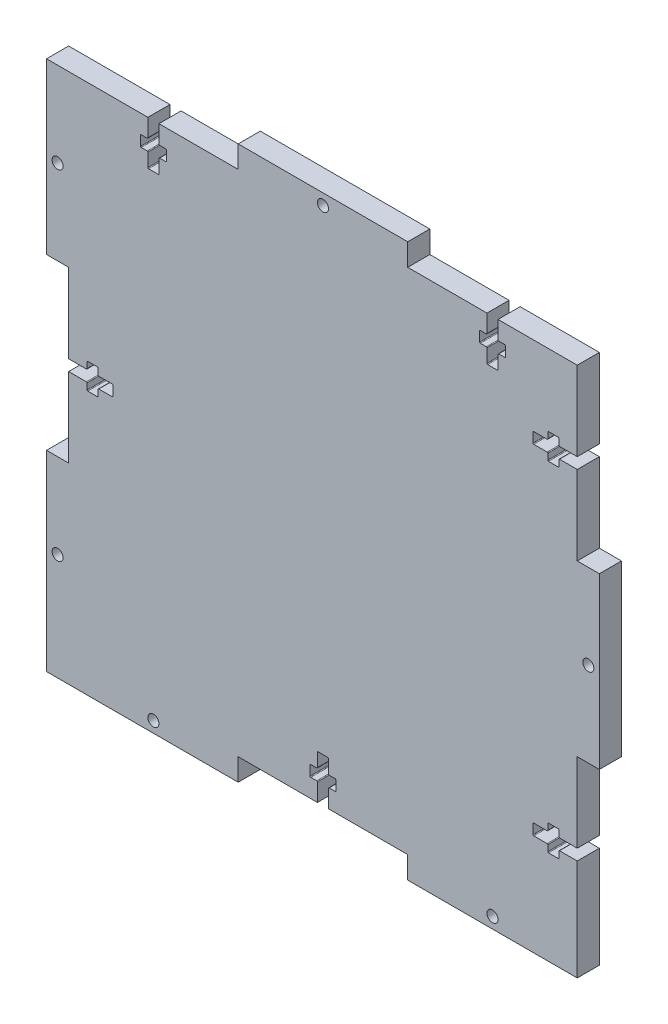
SolidWorks part; units mm, degrees
ref_plane "Front Plane" through (0, 0, 0) normal (0, 0, 1) x (1, 0, 0)
ref_plane "Top Plane" through (0, 0, 0) normal (0, 1, 0) x (1, 0, 0)
ref_plane "Right Plane" through (0, 0, 0) normal (1, 0, 0) x (0, 0, -1)
sketch "Sketch1" plane through (0, 0, 0) normal (0, 0, 1) x (1, 0, 0)
  line L0 (-69, 69) -> (-23, 69)
  line L5 (-75, -75) -> (75, -75) construction
  line L6 (-75, -75) -> (-75, 75) construction
  line L7 (-75, 75) -> (75, 75) construction
  line L8 (75, -75) -> (75, 75) construction
  line L9 (75, 23) -> (69, 23)
  line L10 (69, -23) -> (75, -23)
  line L11 (-69, -69) -> (69, -69) construction
  line L12 (-69, -69) -> (-69, 69) construction
  line L13 (-69, 69) -> (69, 69) construction
  line L14 (69, -69) -> (69, 69) construction
  line L15 (-69, -69) -> (69, 69) construction
  line L16 (69, -69) -> (69, -23)
  line L17 (-23, 69) -> (-23, 75)
  line L18 (-23, 75) -> (23, 75)
  line L19 (23, 75) -> (23, 69)
  line L20 (23, 69) -> (69, 69)
  line L21 (75, -23) -> (75, 23)
  line L22 (69, 23) -> (69, 69)
  line L23 (-75, 23) -> (-69, 23)
  line L24 (-69, 69) -> (-75, 69)
  line L25 (-75, 69) -> (-75, 23)
  line L26 (69, -69) -> (69, -75)
  line L27 (69, -75) -> (23, -75)
  line L28 (23, -75) -> (23, -69)
  line L29 (23, -69) -> (-23, -69)
  line L30 (-23, -69) -> (-23, -75)
  line L31 (-23, -75) -> (-69, -75)
  line L32 (-69, -75) -> (-69, -69) construction
  line L33 (-69, 23) -> (-69, -23)
  line L34 (-69, -23) -> (-75, -23)
  line L35 (-75, -23) -> (-75, -69)
  line L36 (-75, -69) -> (-69, -69) construction
  line L37 (-46, 69) -> (-46, -75) construction
  line L38 (-69, 69) -> (69, -69) construction
  line L39 (-75, -75) -> (-69, -75)
  line L40 (-75, -75) -> (-75, -69)
  point P0 (0, 0)
  point P6 (-7, -7)
  point P26 (0, -75)
  point P27 (-75, 0)
  dimension "D1" = 150
  dimension "D2" = 150
  dimension "D5" = 46
  dimension "D3" = 6
  dimension "D6" = 6
  dimension "D7" = 6
extrude "Box Side" add sketch "Sketch1" along normal blind 6
sketch "Sketch2" plane through (0, 0, 6) normal (0, 0, 1) x (1, 0, 0)
  line L0 (23, 72) -> (-23, 72) construction
  line L1 (23, 75) -> (23, 69) construction
  line L2 (-23, 69) -> (-23, 75) construction
  line L3 (-46, 69) -> (-46, -75) construction
  line L5 (0, 75) -> (0, 69) construction
  line L6 (-23, 75) -> (23, 75) construction
  line L7 (-69, 69) -> (69, 69) construction
  line L16 (-46, 69) -> (-46, -75) construction
  line L21 (0, -69) -> (0, 69) construction
  line L35 (-69, 69) -> (-23, 69) construction
  line L36 (-44.5, 69) -> (-44.5, 64.2)
  line L37 (-44.3, 64) -> (-42.7, 64)
  line L38 (-42.5, 63.8) -> (-42.5, 61.2)
  line L39 (-42.7, 61) -> (-44.3, 61)
  line L40 (-44.5, 60.8) -> (-44.5, 57.2)
  line L46 (-44.7, 57) -> (-47.3, 57)
  line L48 (-44.5, 69) -> (-47.5, 69)
  line L51 (-47.5, 60.8) -> (-47.5, 57.2)
  line L52 (-49.3, 61) -> (-47.7, 61)
  line L53 (-49.5, 63.8) -> (-49.5, 61.2)
  line L54 (-47.7, 64) -> (-49.3, 64)
  line L55 (-47.5, 69) -> (-47.5, 64.2)
  line L56 (47.5, 69) -> (47.5, 64.2)
  line L57 (47.7, 64) -> (49.3, 64)
  line L58 (49.5, 63.8) -> (49.5, 61.2)
  line L59 (49.3, 61) -> (47.7, 61)
  line L60 (47.5, 60.8) -> (47.5, 57.2)
  line L61 (44.5, 69) -> (47.5, 69)
  line L62 (44.7, 57) -> (47.3, 57)
  line L63 (44.5, 60.8) -> (44.5, 57.2)
  line L64 (42.7, 61) -> (44.3, 61)
  line L65 (42.5, 63.8) -> (42.5, 61.2)
  line L66 (44.3, 64) -> (42.7, 64)
  line L67 (44.5, 69) -> (44.5, 64.2)
  line L68 (-69, -69) -> (69, 69) construction
  line L69 (-69, -69) -> (69, 69) construction
  line L70 (75, 0) -> (69, 0) construction
  line L71 (72, 23) -> (72, -23) construction
  line L72 (69, 44.5) -> (64.2, 44.5)
  line L73 (64, 44.3) -> (64, 42.7)
  line L74 (63.8, 42.5) -> (61.2, 42.5)
  line L75 (61, 42.7) -> (61, 44.3)
  line L76 (60.8, 44.5) -> (57.2, 44.5)
  line L77 (57, 44.7) -> (57, 47.3)
  line L78 (69, 44.5) -> (69, 47.5)
  line L79 (60.8, 47.5) -> (57.2, 47.5)
  line L80 (61, 49.3) -> (61, 47.7)
  line L81 (63.8, 49.5) -> (61.2, 49.5)
  line L82 (64, 47.7) -> (64, 49.3)
  line L83 (69, 47.5) -> (64.2, 47.5)
  line L84 (69, -47.5) -> (64.2, -47.5)
  line L85 (64, -47.7) -> (64, -49.3)
  line L86 (63.8, -49.5) -> (61.2, -49.5)
  line L87 (61, -49.3) -> (61, -47.7)
  line L88 (60.8, -47.5) -> (57.2, -47.5)
  line L89 (69, -44.5) -> (69, -47.5)
  line L90 (57, -44.7) -> (57, -47.3)
  line L91 (60.8, -44.5) -> (57.2, -44.5)
  line L92 (61, -42.7) -> (61, -44.3)
  line L93 (63.8, -42.5) -> (61.2, -42.5)
  line L94 (64, -44.3) -> (64, -42.7)
  line L95 (69, -44.5) -> (64.2, -44.5)
  line L120 (-69, 69) -> (69, -69) construction
  line L121 (-69, 69) -> (69, -69) construction
  line L122 (-1.5, -69) -> (1.5, -69)
  line L123 (-23, -69) -> (23, -69) construction
  line L124 (1.5, -69) -> (1.5, -64.2)
  line L125 (1.7, -64) -> (3.3, -64)
  line L126 (3.5, -63.8) -> (3.5, -61.2)
  line L127 (3.3, -61) -> (1.7, -61)
  line L128 (1.5, -60.8) -> (1.5, -57.2)
  line L129 (1.3, -57) -> (-1.3, -57)
  line L130 (-1.5, -60.8) -> (-1.5, -57.2)
  line L131 (-3.3, -61) -> (-1.7, -61)
  line L132 (-3.5, -63.8) -> (-3.5, -61.2)
  line L133 (-1.7, -64) -> (-3.3, -64)
  line L134 (-1.5, -69) -> (-1.5, -64.2)
  line L135 (-69, -1.5) -> (-64.2, -1.5)
  line L136 (-64, -1.7) -> (-64, -3.3)
  line L137 (-63.8, -3.5) -> (-61.2, -3.5)
  line L138 (-61, -3.3) -> (-61, -1.7)
  line L139 (-60.8, -1.5) -> (-57.2, -1.5)
  line L140 (-57, 1.3) -> (-57, -1.3)
  line L141 (-60.8, 1.5) -> (-57.2, 1.5)
  line L142 (-61, 3.3) -> (-61, 1.7)
  line L143 (-63.8, 3.5) -> (-61.2, 3.5)
  line L144 (-64, 1.7) -> (-64, 3.3)
  line L145 (-69, 1.5) -> (-64.2, 1.5)
  line L146 (-69, -1.5) -> (-69, 1.5)
  line L147 (-69, -72) -> (-23, -72) construction
  line L148 (-23, 69) -> (-75, 69) construction
  line L149 (-23, -75) -> (-23, -69) construction
  line L150 (-69, -69) -> (-69, -75) construction
  line L151 (-75, -75) -> (-23, -75) construction
  circle A0 centre (0, 72) radius 1.5
  arc A1 (-44.5, 57.2) -> (-44.7, 57) centre (-44.7, 57.2) cw
  arc A2 (-44.3, 61) -> (-44.5, 60.8) centre (-44.3, 60.8) ccw
  arc A3 (-42.5, 61.2) -> (-42.7, 61) centre (-42.7, 61.2) cw
  arc A4 (-42.7, 64) -> (-42.5, 63.8) centre (-42.7, 63.8) cw
  arc A5 (-44.5, 64.2) -> (-44.3, 64) centre (-44.3, 64.2) ccw
  arc A6 (-47.5, 64.2) -> (-47.7, 64) centre (-47.7, 64.2) cw
  arc A7 (-49.3, 64) -> (-49.5, 63.8) centre (-49.3, 63.8) ccw
  arc A8 (-49.5, 61.2) -> (-49.3, 61) centre (-49.3, 61.2) ccw
  arc A9 (-47.7, 61) -> (-47.5, 60.8) centre (-47.7, 60.8) cw
  arc A10 (-47.5, 57.2) -> (-47.3, 57) centre (-47.3, 57.2) ccw
  arc A11 (47.5, 57.2) -> (47.3, 57) centre (47.3, 57.2) cw
  arc A12 (47.7, 61) -> (47.5, 60.8) centre (47.7, 60.8) ccw
  arc A13 (49.5, 61.2) -> (49.3, 61) centre (49.3, 61.2) cw
  arc A14 (49.3, 64) -> (49.5, 63.8) centre (49.3, 63.8) cw
  arc A15 (47.5, 64.2) -> (47.7, 64) centre (47.7, 64.2) ccw
  arc A16 (44.5, 64.2) -> (44.3, 64) centre (44.3, 64.2) cw
  arc A17 (42.7, 64) -> (42.5, 63.8) centre (42.7, 63.8) ccw
  arc A18 (42.5, 61.2) -> (42.7, 61) centre (42.7, 61.2) ccw
  arc A19 (44.3, 61) -> (44.5, 60.8) centre (44.3, 60.8) cw
  arc A20 (44.5, 57.2) -> (44.7, 57) centre (44.7, 57.2) ccw
  arc A21 (57.2, 44.5) -> (57, 44.7) centre (57.2, 44.7) cw
  arc A22 (61, 44.3) -> (60.8, 44.5) centre (60.8, 44.3) ccw
  arc A23 (61.2, 42.5) -> (61, 42.7) centre (61.2, 42.7) cw
  arc A24 (64, 42.7) -> (63.8, 42.5) centre (63.8, 42.7) cw
  arc A25 (64.2, 44.5) -> (64, 44.3) centre (64.2, 44.3) ccw
  arc A26 (64.2, 47.5) -> (64, 47.7) centre (64.2, 47.7) cw
  arc A27 (64, 49.3) -> (63.8, 49.5) centre (63.8, 49.3) ccw
  arc A28 (61.2, 49.5) -> (61, 49.3) centre (61.2, 49.3) ccw
  arc A29 (61, 47.7) -> (60.8, 47.5) centre (60.8, 47.7) cw
  arc A30 (57.2, 47.5) -> (57, 47.3) centre (57.2, 47.3) ccw
  arc A31 (57.2, -47.5) -> (57, -47.3) centre (57.2, -47.3) cw
  arc A32 (61, -47.7) -> (60.8, -47.5) centre (60.8, -47.7) ccw
  arc A33 (61.2, -49.5) -> (61, -49.3) centre (61.2, -49.3) cw
  arc A34 (64, -49.3) -> (63.8, -49.5) centre (63.8, -49.3) cw
  arc A35 (64.2, -47.5) -> (64, -47.7) centre (64.2, -47.7) ccw
  arc A36 (64.2, -44.5) -> (64, -44.3) centre (64.2, -44.3) cw
  arc A37 (64, -42.7) -> (63.8, -42.5) centre (63.8, -42.7) ccw
  arc A38 (61.2, -42.5) -> (61, -42.7) centre (61.2, -42.7) ccw
  arc A39 (61, -44.3) -> (60.8, -44.5) centre (60.8, -44.3) cw
  arc A40 (57.2, -44.5) -> (57, -44.7) centre (57.2, -44.7) ccw
  circle A41 centre (72, 0) radius 1.5
  arc A62 (1.5, -57.2) -> (1.3, -57) centre (1.3, -57.2) ccw
  arc A63 (1.7, -61) -> (1.5, -60.8) centre (1.7, -60.8) cw
  arc A64 (3.5, -61.2) -> (3.3, -61) centre (3.3, -61.2) ccw
  arc A65 (3.3, -64) -> (3.5, -63.8) centre (3.3, -63.8) ccw
  arc A66 (1.5, -64.2) -> (1.7, -64) centre (1.7, -64.2) cw
  arc A67 (-1.5, -64.2) -> (-1.7, -64) centre (-1.7, -64.2) ccw
  arc A68 (-3.3, -64) -> (-3.5, -63.8) centre (-3.3, -63.8) cw
  arc A69 (-3.5, -61.2) -> (-3.3, -61) centre (-3.3, -61.2) cw
  arc A70 (-1.7, -61) -> (-1.5, -60.8) centre (-1.7, -60.8) ccw
  arc A71 (-1.5, -57.2) -> (-1.3, -57) centre (-1.3, -57.2) cw
  arc A72 (-57.2, -1.5) -> (-57, -1.3) centre (-57.2, -1.3) ccw
  arc A73 (-61, -1.7) -> (-60.8, -1.5) centre (-60.8, -1.7) cw
  arc A74 (-61.2, -3.5) -> (-61, -3.3) centre (-61.2, -3.3) ccw
  arc A75 (-64, -3.3) -> (-63.8, -3.5) centre (-63.8, -3.3) ccw
  arc A76 (-64.2, -1.5) -> (-64, -1.7) centre (-64.2, -1.7) cw
  arc A77 (-64.2, 1.5) -> (-64, 1.7) centre (-64.2, 1.7) ccw
  arc A78 (-64, 3.3) -> (-63.8, 3.5) centre (-63.8, 3.3) cw
  arc A79 (-61.2, 3.5) -> (-61, 3.3) centre (-61.2, 3.3) cw
  arc A80 (-61, 1.7) -> (-60.8, 1.5) centre (-60.8, 1.7) ccw
  arc A81 (-57.2, 1.5) -> (-57, 1.3) centre (-57.2, 1.3) cw
  circle A82 centre (-46, -72) radius 1.5
  circle A83 centre (46, -72) radius 1.5
  circle A84 centre (-72, 46) radius 1.5
  circle A85 centre (-72, -46) radius 1.5
  point P6 (0, 72)
  point P38 (0, 0)
  point P56 (-46, 57)
  point P88 (46, 57)
  point P161 (57, 46)
  point P162 (57, -46)
  point P198 (0, -57)
  point P231 (-57, 0)
  point P234 (-42.5, 62.5)
  dimension "D1" = 3
  dimension "D2" = 0.2
  dimension "D8" = 0.2
  dimension "D14" = 3
  dimension "D4" = 3
  dimension "D7" = 1.5
  dimension "D10" = 3
  dimension "D12" = 1.5
  dimension "D9" = 12
  dimension "D11" = 5
  dimension "D13" = 7
  dimension "D3" = 12
  dimension "D5" = 7
  dimension "D6" = 5
extrude "Screw Cut-outs" cut sketch "Sketch2" against normal through all
equation "\"filletRadius\"=0.2"
equation "\"D8@Sketch2\"=\"filletRadius\""
equation "\"D2@Sketch2\"=\"filletRadius\""
equation "\"fingerWidth\"= 46"
equation "\"D5@Sketch1\"=\"fingerWidth\""
equation "\"WallThickness\"= 6"
equation "\"D3@Sketch1\"=\"WallThickness\""
equation "\"D6@Sketch1\"=\"WallThickness\""
equation "\"D7@Sketch1\"=\"WallThickness\""
equation "\"D1@Box Side\"=\"WallThickness\""
equation "\"M3\"= 3"
equation "\"D14@Sketch2\"=\"M3\""
equation "\"D1@Sketch2\"=\"M3\""
equation "\"D12@Sketch2\"=\"M3\"/2"
equation "\"NutThickness\"=3"
equation "\"D10@Sketch2\"=\"NutThickness\""
equation "\"BoltLength\"= 12"
equation "\"D9@Sketch2\"=\"BoltLength\""
equation "\"DistanceToNut\"= 5"
equation "\"D11@Sketch2\"=\"DistanceToNut\""
equation "\"D13@Sketch2\"=\"NutWidth\""
equation "\"D7@Sketch2\"=\"M3\"/2"
equation "\"D4@Sketch2\"=\"NutThickness\""
equation "\"D3@Sketch2\"=\"BoltLength\""
equation "\"D5@Sketch2\"=\"NutWidth\""
equation "\"D6@Sketch2\"=\"DistanceToNut\""
equation "\"sideLength\"=150"
equation "\"D1@Sketch1\"=\"sideLength\""
equation "\"D2@Sketch1\"=\"sideLength\""
equation "\"NutWidth\"=7"
